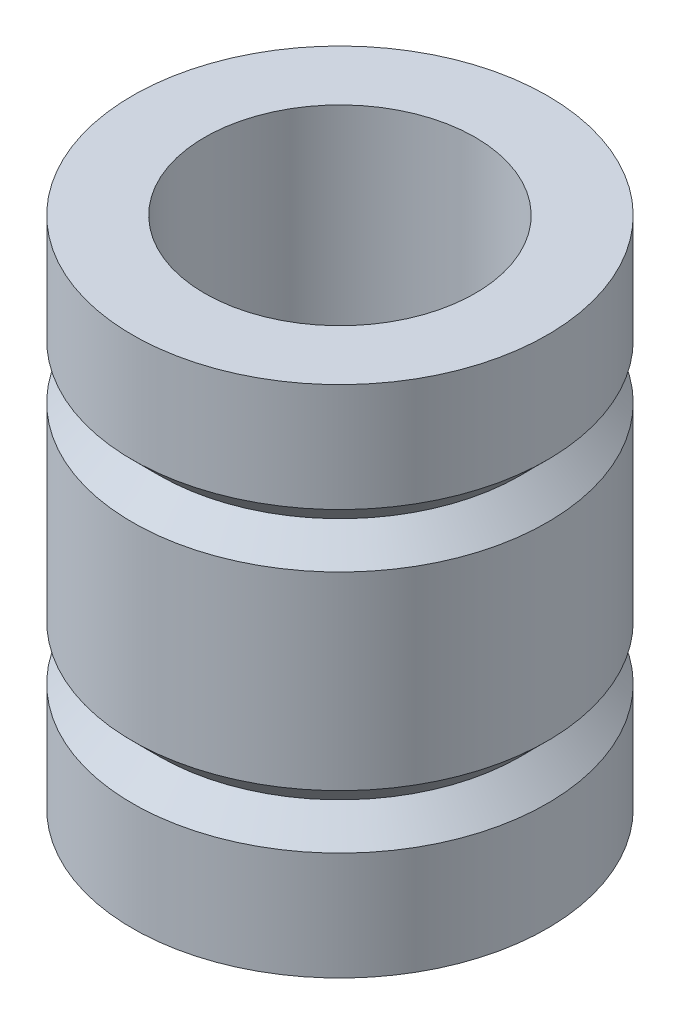
SolidWorks part; units mm, degrees
ref_plane "Front Plane" through (0, 0, 0) normal (0, 0, 1) x (1, 0, 0)
ref_plane "Top Plane" through (0, 0, 0) normal (0, 1, 0) x (1, 0, 0)
ref_plane "Right Plane" through (0, 0, 0) normal (1, 0, 0) x (0, 0, -1)
sketch "Sketch1" plane through (0, 0, 0) normal (0, 0, 1) x (1, 0, 0)
  line L0 (1.5, 0) -> (2.3, 0)
  line L1 (2.3, 0) -> (2.3, -1.2)
  line L2 (2.3, -1.2) -> (2, -1.5)
  line L3 (2, -1.5) -> (2.3, -1.8)
  line L4 (2.3, -1.8) -> (2.3, -3.9)
  line L5 (2.3, -3.9) -> (2, -4.2)
  line L6 (2, -4.2) -> (2.3, -4.5)
  line L7 (2.3, -4.5) -> (2.3, -5.7)
  line L8 (2.3, -5.7) -> (1.5, -5.7)
  line L9 (1.5, -5.7) -> (1.5, 0)
  line L10 (0, -10) -> (0, 1000) construction
revolve "Revolve1" add sketch "Sketch1" angle 360 about L10
cosmetic thread "Cosmetic Thread1"
